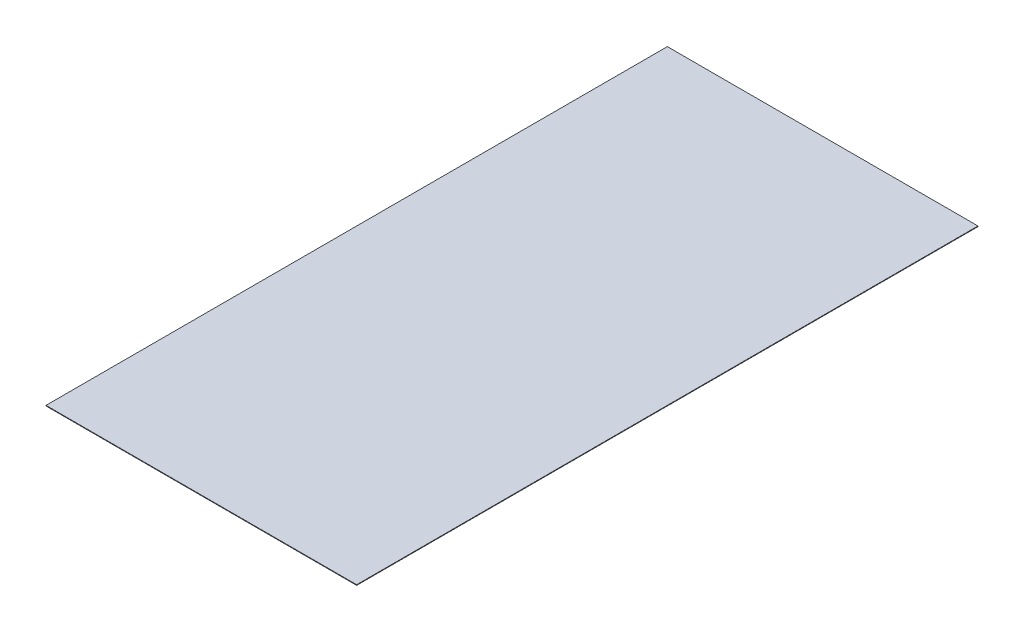
SolidWorks part; units mm, degrees
material "ASTM A36 Acero"
ref_plane "Alzado" through (0, 0, 0) normal (0, 0, 1) x (1, 0, 0)
ref_plane "Planta" through (0, 0, 0) normal (0, 1, 0) x (1, 0, 0)
ref_plane "Vista lateral" through (0, 0, 0) normal (1, 0, 0) x (0, 0, -1)
sketch "Croquis1" plane through (0, 0, 0) normal (0, 1, 0) x (1, 0, 0)
  line L1 (-609.6, -1219.2) -> (609.6, -1219.2)
  line L2 (-609.6, -1219.2) -> (-609.6, 1219.2)
  line L3 (-609.6, 1219.2) -> (609.6, 1219.2)
  line L4 (609.6, -1219.2) -> (609.6, 1219.2)
  line L5 (-609.6, -1219.2) -> (609.6, 1219.2) construction
  line L6 (-609.6, 1219.2) -> (609.6, -1219.2) construction
  point P0 (0, 0)
  dimension "D1" = 2438.4
  dimension "D2" = 1219.2
extrude "Saliente-Extruir1" add sketch "Croquis1" along normal blind 2.3
